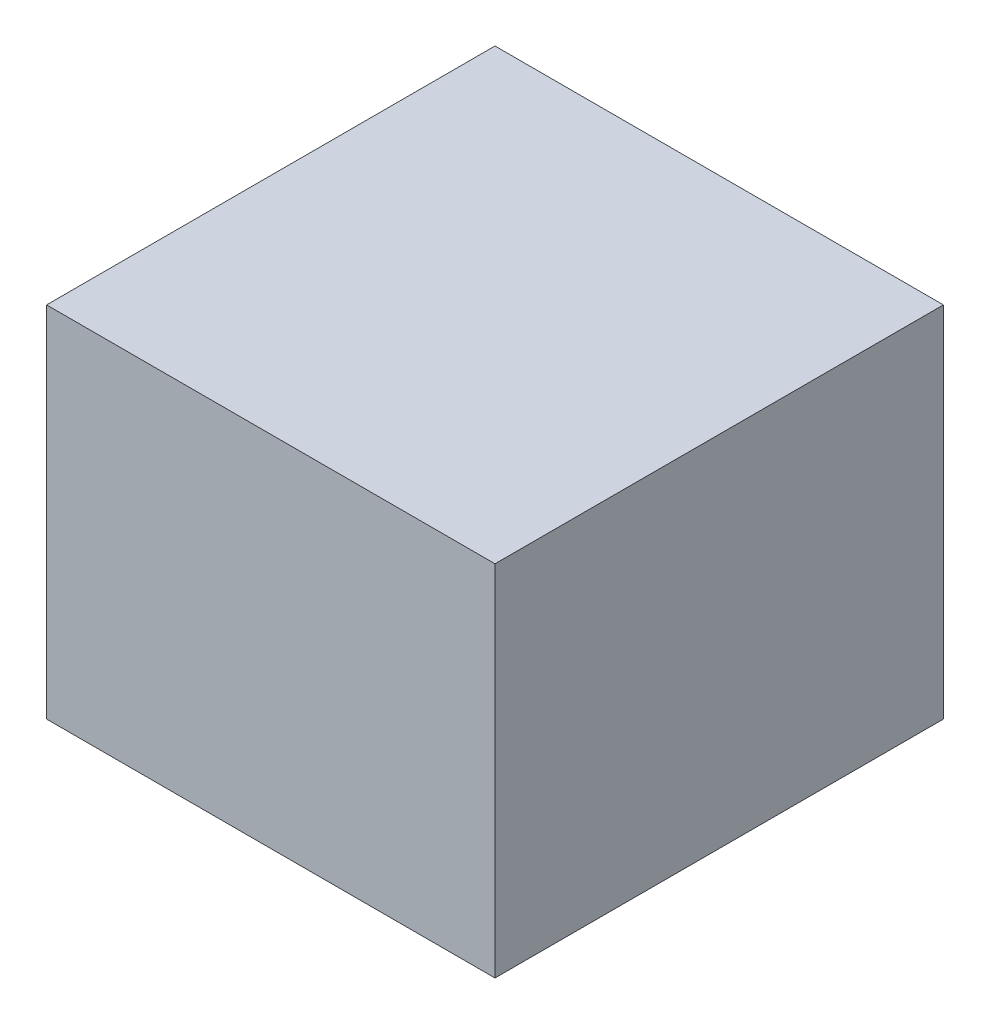
SolidWorks part; units mm, degrees
ref_plane "Front Plane" through (0, 0, 0) normal (0, 0, 1) x (1, 0, 0)
ref_plane "Top Plane" through (0, 0, 0) normal (0, 1, 0) x (1, 0, 0)
ref_plane "Right Plane" through (0, 0, 0) normal (1, 0, 0) x (0, 0, -1)
sketch "Sketch1" plane through (0, 0, 0) normal (0, 1, 0) x (1, 0, 0)
  line L1 (127, 127) -> (-127, 127)
  line L2 (127, 127) -> (127, -127)
  line L3 (127, -127) -> (-127, -127)
  line L4 (-127, 127) -> (-127, -127)
  line L5 (127, 127) -> (-127, -127) construction
  line L6 (127, -127) -> (-127, 127) construction
  point P0 (0, 0)
  dimension "D1" = 254
  dimension "D2" = 254
extrude "Boss-Extrude1" add sketch "Sketch1" along normal blind 203.2
